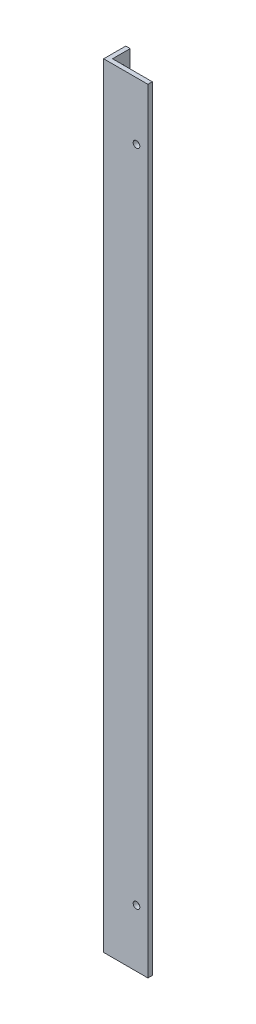
SolidWorks part; units mm, degrees
ref_plane "Front Plane" through (0, 0, 0) normal (0, 0, 1) x (1, 0, 0)
ref_plane "Top Plane" through (0, 0, 0) normal (0, 1, 0) x (1, 0, 0)
ref_plane "Right Plane" through (0, 0, 0) normal (1, 0, 0) x (0, 0, -1)
sketch "Sketch1" plane through (0, 0, 0) normal (0, 1, 0) x (1, 0, 0)
  line L0 (0, 0) -> (0, 10)
  line L1 (0, 10) -> (2, 10)
  line L2 (2, 10) -> (2, 2)
  line L3 (2, 2) -> (20, 2)
  line L4 (20, 2) -> (20, 0)
  line L5 (20, 0) -> (0, 0)
extrude "Boss-Extrude1" add sketch "Sketch1" along normal up to surface (350 mm away)
hole_wizard "Ø3.0 (3) Diameter Slot1" positions "Sketch2" profile "Sketch3" size "Ø3.0" standard "ISO" slot yes end condition through all
sketch "Sketch2" plane through (0, 0, 0) normal (0, 0, 1) x (1, 0, 0)
  point P0 (14.8385, 25.9101)
  point P2 (14.8385, 323.8663)
sketch "Sketch3" plane through (14.8385, 25.9101, 0) normal (1, 0, 0) x (0, -1, 0)
  line L0 (0, 0) -> (0, 10)
  line L1 (0, 10) -> (1.5, 10)
  line L2 (1.5, 10) -> (1.5, 0)
  line L5 (1.5, 0) -> (0, 0)
  line L11 (0, -6.35) -> (0, 107.95) construction
  dimension "Thru Hole Dia." = 3
  dimension "Thru Hole Depth" = 10
hole_wizard "Ø3.0 (3) Diameter Hole2" positions "Sketch5" profile "Sketch6" hole size "Ø3.0" standard "ISO"
sketch "Sketch5" plane through (0, 128.862, -176.68) normal (-1, 0, 0) x (0, 1, 0)
  circle A0 centre (-108.862, -170.68) radius 1.5
  circle A1 centre (215.138, -170.68) radius 1.5
  circle A2 centre (201.138, -170.68) radius 1.5
  point P0 (-122.862, -170.68)
  point P1 (-108.862, -170.68)
  point P3 (215.138, -170.68)
  point P7 (201.138, -170.68)
  point P9 (201.138, -170.68)
  point P10 (215.138, -170.68)
sketch "Sketch6" plane through (0, 6, -6) normal (0, 1, 0) x (0, 0, 1)
  line L0 (0, 0) -> (0, 4)
  line L1 (0, 4) -> (1.5, 4)
  line L2 (1.5, 4) -> (1.5, 0)
  line L5 (1.5, 0) -> (0, 0)
  line L11 (0, -6.35) -> (0, 107.95) construction
  dimension "Thru Hole Dia." = 3
  dimension "Thru Hole Depth" = 4
